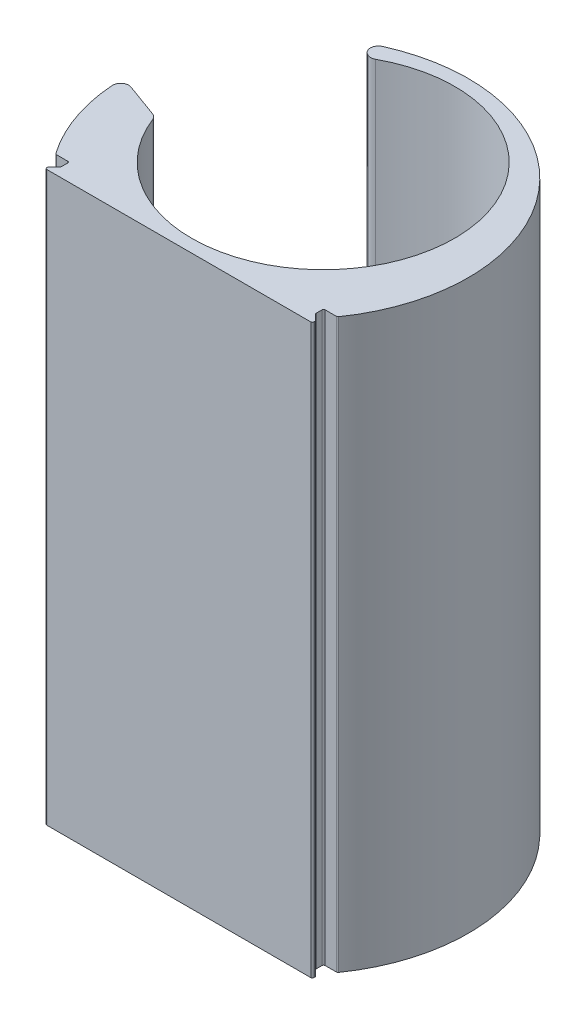
SolidWorks part; units mm, degrees
ref_plane "Front Plane" through (0, 0, 0) normal (0, 0, 1) x (1, 0, 0)
ref_plane "Top Plane" through (0, 0, 0) normal (0, 1, 0) x (1, 0, 0)
ref_plane "Right Plane" through (0, 0, 0) normal (1, 0, 0) x (0, 0, -1)
sketch "Sketch1" plane through (0, 0, 0) normal (0, 1, 0) x (1, 0, 0)
  line L0 (-19.1484, -30.0361) -> (-16.2484, -30.0361) construction
  line L1 (-16.2484, -30.0361) -> (-18.4484, -27.8361) construction
  line L2 (-18.4484, -27.8361) -> (-19.9484, -27.8361) construction
  line L3 (-19.9484, -27.8361) -> (-19.9484, -28.6361) construction
  line L4 (-19.9484, -28.6361) -> (-19.1484, -29.4361) construction
  line L5 (-19.1484, -29.4361) -> (-19.1484, -30.0361) construction
  line L6 (-55.6484, -30.0361) -> (-52.7484, -30.0361) construction
  line L7 (-52.7484, -30.0361) -> (-52.7484, -29.4361) construction
  line L8 (-52.7484, -29.4361) -> (-51.9484, -28.6361) construction
  line L9 (-51.9484, -28.6361) -> (-51.9484, -27.8361) construction
  line L10 (-51.9484, -27.8361) -> (-53.4484, -27.8361) construction
  line L11 (-53.4484, -27.8361) -> (-55.6484, -30.0361) construction
  line L12 (-19.2984, -30.1861) -> (-15.8863, -30.1861) construction
  line L13 (-15.8863, -30.1861) -> (-18.3863, -27.6861) construction
  line L14 (-18.3863, -27.6861) -> (-20.0984, -27.6861)
  line L15 (-20.0984, -27.6861) -> (-20.0984, -28.6982)
  line L16 (-20.0984, -28.6982) -> (-19.2984, -29.4982)
  line L17 (-19.2984, -29.4982) -> (-19.2984, -29.8861)
  line L18 (-56.0106, -30.1861) -> (-52.5984, -30.1861) construction
  line L19 (-52.5984, -29.8861) -> (-52.5984, -29.4982)
  line L20 (-52.5984, -29.4982) -> (-51.7984, -28.6982)
  line L21 (-51.7984, -28.6982) -> (-51.7984, -27.6861)
  line L22 (-51.7984, -27.6861) -> (-53.5106, -27.6861)
  line L23 (-53.5106, -27.6861) -> (-56.0106, -30.1861) construction
  line L24 (-52.5984, -29.8861) -> (-19.2984, -29.8861)
  line L25 (-19.2984, -29.4982) -> (-19.2984, -30.1861) construction
  line L26 (-52.5984, -30.1861) -> (-52.5984, -29.4982) construction
  circle A1 centre (-35.9484, -11.8861) radius 16.4
  arc A2 (-53.5106, -27.6861) -> (-18.3863, -27.6861) centre (-35.9484, -15.2836) cw
  dimension "D4" = 32.8
  dimension "D5" = 21.5
  dimension "D2" = 0.15
  dimension "D3" = 18
  dimension "D1" = 0.15
extrude "Boss-Extrude1" add sketch "Sketch1" along normal blind 70
sketch "Sketch2" plane through (0, 0, 0) normal (0, -1, 0) x (1, 0, 0)
  line L9 (-18.3863, 27.6861) -> (-20.0984, 27.6861)
  line L10 (-20.0984, 27.6861) -> (-20.0984, 28.6982)
  line L11 (-20.0984, 28.6982) -> (-19.2984, 29.4982)
  line L12 (-19.2984, 29.4982) -> (-19.2984, 29.8861)
  line L13 (-19.2984, 29.8861) -> (-52.5984, 29.8861)
  line L14 (-52.5984, 29.8861) -> (-52.5984, 29.4982)
  line L15 (-52.5984, 29.4982) -> (-51.7984, 28.6982)
  line L16 (-51.7984, 28.6982) -> (-51.7984, 27.6861)
  line L17 (-51.7984, 27.6861) -> (-53.5106, 27.6861)
  line L18 (-18.3863, 27.6861) -> (-20.0984, 27.6861)
  line L19 (-20.0984, 27.6861) -> (-20.0984, 28.6982)
  line L20 (-20.0984, 28.6982) -> (-19.2984, 29.4982)
  line L21 (-19.2984, 29.4982) -> (-19.2984, 29.8861)
  line L22 (-19.2984, 29.8861) -> (-52.5984, 29.8861)
  line L23 (-52.5984, 29.8861) -> (-52.5984, 29.4982)
  line L24 (-52.5984, 29.4982) -> (-51.7984, 28.6982)
  line L25 (-51.7984, 28.6982) -> (-51.7984, 27.6861)
  line L26 (-51.7984, 27.6861) -> (-53.5106, 27.6861)
  arc A1 (-53.5106, 27.6861) -> (-18.3863, 27.6861) centre (-35.9484, 15.2836) ccw
  arc A2 (-53.5106, 27.6861) -> (-18.3863, 27.6861) centre (-35.9484, 15.2836) ccw
  dimension "D1" = 0
extrude "Boss-Extrude2" add sketch "Sketch2" along normal blind 0.8
sketch "Sketch3" plane through (0, 70, 0) normal (0, 1, 0) x (1, 0, 0)
  line L0 (-49.616, -18.0854) -> (-42.4335, 1.6482)
  line L1 (-49.616, -18.0854) -> (-64.5965, -12.6329)
  line L2 (-42.4335, 1.6482) -> (-57.4141, 7.1006)
  line L3 (-64.5965, -12.6329) -> (-57.4141, 7.1006)
  line L4 (-35.6319, -29.8861) -> (-67.0908, -29.8861) construction
  line L5 (-52.5984, -29.8861) -> (-19.2984, -29.8861) construction
  line L6 (-35.9484, -11.8861) -> (-46.0248, -8.2186) construction
  dimension "D1" = 20
  dimension "D2" = 21
extrude "Cut-Extrude1" cut sketch "Sketch3" against normal blind 64
fillet "Fillet1" radius 1 4 edges at (-57.4484, 38, 15.2346) (-46.8416, 38, -3.2526) (-51.3779, 38, 17.4441) (-44.1955, 38, -2.2895)
fillet "Fillet2" radius 0.2 10 edges at (-18.3863, 34.6, 27.6861) (-20.0984, 34.6, 27.6861) (-20.0984, 34.6, 28.6982) (-19.2984, 34.6, 29.4982) (-19.2984, 34.6, 29.8861) (-52.5984, 34.6, 29.8861) (-52.5984, 34.6, 29.4982) (-51.7984, 34.6, 28.6982) (-51.7984, 34.6, 27.6861) (-53.5106, 34.6, 27.6861)
sketch "Sketch4" plane through (0, 0, 0) normal (1, 0, 0) x (0, 0, -1)
  line L0 (5.2002, -1.5456) -> (6.9524, 1.5449)
  line L1 (6.9524, 1.5449) -> (6.9524, -1.5456)
  line L2 (6.9524, -1.5456) -> (5.2002, -1.5456)
extrude "Cut-Extrude2" [suppressed] cut sketch "Sketch4" against normal through all both and the other way through all
